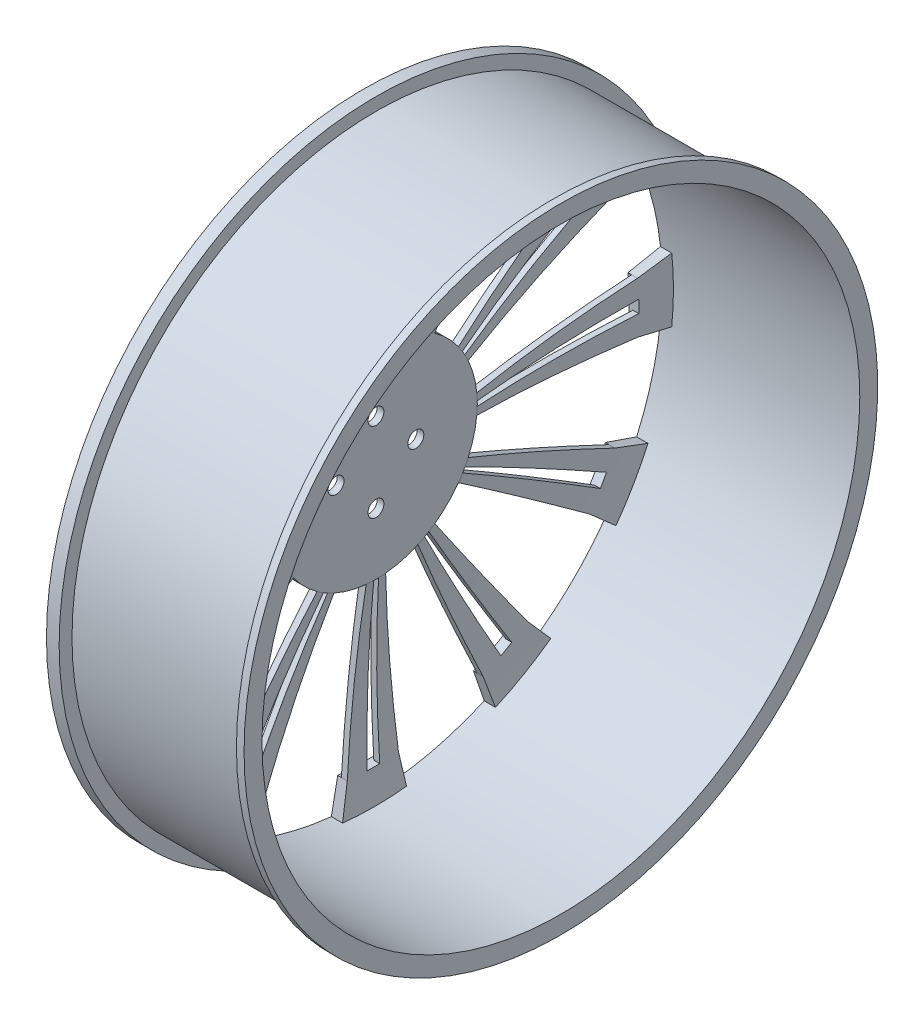
SolidWorks part; units mm, degrees
material "Stainless Steel (ferritic)"
ref_plane "Front Plane" through (0, 0, 0) normal (0, 0, 1) x (1, 0, 0)
ref_plane "Top Plane" through (0, 0, 0) normal (0, 1, 0) x (1, 0, 0)
ref_plane "Right Plane" through (0, 0, 0) normal (1, 0, 0) x (0, 0, -1)
sketch "Sketch1" plane through (0, 0, 0) normal (0, 1, 0) x (1, 0, 0)
  line L0 (0, 0) -> (0, 152.4) construction
  line L1 (-44.45, 152.4) -> (44.45, 152.4)
  line L2 (44.45, 152.4) -> (44.45, 158.8516)
  line L3 (44.45, 158.8516) -> (48.26, 158.8516)
  line L4 (48.26, 158.8516) -> (48.26, 149.86)
  line L6 (-48.26, 158.8516) -> (-48.26, 149.86)
  line L7 (-44.45, 158.8516) -> (-48.26, 158.8516)
  line L8 (-44.45, 152.4) -> (-44.45, 158.8516)
  line L11 (-115.1983, 0) -> (-44.4652, 0) construction
  line L12 (-44.4652, 50.8) -> (-44.4652, 0)
  line L13 (-47.8645, 50.8) -> (-47.8645, 0)
  line L14 (-47.8645, 0) -> (-44.4652, 0)
  line L15 (-45.1655, 149.86) -> (48.26, 149.86)
  line L16 (-44.45, 0) -> (115.1983, 0) construction
  arc A0 (-48.26, 149.86) -> (-47.8645, 50.8) centre (824.7529, 103.8144) ccw
  arc A1 (-45.1655, 149.86) -> (-44.4652, 50.8) centre (663.4897, 105.3377) ccw
  point P6 (0, 152.4)
  point P11 (0, 149.86)
  point P13 (44.45, 155.6258)
  point P26 (0, 0)
  dimension "D5" = 3.4145
  dimension "D7" = 874.2264
  dimension "D8" = 710.0525
  dimension "D1" = 3.81
  dimension "D2" = 88.9
  dimension "D3" = 152.4
  dimension "D4" = 6.4516
  dimension "D6" = 93.4255
  dimension "D9" = 50.8
  dimension "D10" = 50.8
revolve "Revolve2" add sketch "Sketch1" angle 360 about L16
sketch "Sketch2" plane through (-48.26, 0, 0) normal (-1, 0, 0) x (0, 0, 1)
  line L0 (-137.0496, 60.6253) -> (-121.3619, 55.2587)
  line L1 (-149.0011, 16.0218) -> (-132.7318, 12.8255)
  line L2 (-149.0011, -16.0218) -> (-132.7318, -12.8255)
  line L3 (-121.0278, 88.3758) -> (-108.5364, 77.4731)
  line L4 (-88.3758, 121.0278) -> (-77.4731, 108.5364)
  line L5 (-60.6253, 137.0496) -> (-55.2587, 121.3619)
  line L6 (-16.0218, 149.0011) -> (-12.8255, 132.7318)
  line L7 (16.0218, 149.0011) -> (12.8255, 132.7318)
  line L8 (60.6253, 137.0496) -> (55.2587, 121.3619)
  line L9 (88.3758, 121.0278) -> (77.4731, 108.5364)
  line L10 (121.0278, 88.3758) -> (108.5364, 77.4731)
  line L11 (137.0496, 60.6253) -> (121.3619, 55.2587)
  line L12 (149.0011, 16.0218) -> (132.7318, 12.8255)
  line L13 (149.0011, -16.0218) -> (132.7318, -12.8255)
  line L14 (137.0496, -60.6253) -> (121.3619, -55.2587)
  line L15 (121.0278, -88.3758) -> (108.5364, -77.4731)
  line L16 (88.3758, -121.0278) -> (77.4731, -108.5364)
  line L17 (60.6253, -137.0496) -> (55.2587, -121.3619)
  line L18 (16.0218, -149.0011) -> (12.8255, -132.7318)
  line L19 (-16.0218, -149.0011) -> (-12.8255, -132.7318)
  line L20 (-60.6253, -137.0496) -> (-55.2587, -121.3619)
  line L21 (-88.3758, -121.0278) -> (-77.4731, -108.5364)
  line L22 (-121.0278, -88.3758) -> (-108.5364, -77.4731)
  line L23 (-137.0496, -60.6253) -> (-121.3619, -55.2587)
  arc A1 (-132.7318, 12.8255) -> (-132.7318, -12.8255) centre (0, 0) ccw
  arc A3 (-108.5364, 77.4731) -> (-121.3619, 55.2587) centre (0, 0) ccw
  arc A5 (-55.2587, 121.3619) -> (-77.4731, 108.5364) centre (0, 0) ccw
  arc A7 (12.8255, 132.7318) -> (-12.8255, 132.7318) centre (0, 0) ccw
  arc A9 (77.4731, 108.5364) -> (55.2587, 121.3619) centre (0, 0) ccw
  arc A11 (121.3619, 55.2587) -> (108.5364, 77.4731) centre (0, 0) ccw
  arc A13 (132.7318, -12.8255) -> (132.7318, 12.8255) centre (0, 0) ccw
  arc A15 (108.5364, -77.4731) -> (121.3619, -55.2587) centre (0, 0) ccw
  arc A17 (55.2587, -121.3619) -> (77.4731, -108.5364) centre (0, 0) ccw
  arc A19 (-12.8255, -132.7318) -> (12.8255, -132.7318) centre (0, 0) ccw
  arc A21 (-77.4731, -108.5364) -> (-55.2587, -121.3619) centre (0, 0) ccw
  arc A23 (-121.3619, -55.2587) -> (-108.5364, -77.4731) centre (0, 0) ccw
  circle A24 centre (0, 0) radius 158.8516
  arc A25 (-149.0011, -16.0218) -> (-137.0496, -60.6253) centre (0, 0) ccw
  arc A26 (-137.0496, 60.6253) -> (-149.0011, 16.0218) centre (0, 0) ccw
  arc A27 (-88.3758, 121.0278) -> (-121.0278, 88.3758) centre (0, 0) ccw
  arc A28 (-16.0218, 149.0011) -> (-60.6253, 137.0496) centre (0, 0) ccw
  arc A29 (60.6253, 137.0496) -> (16.0218, 149.0011) centre (0, 0) ccw
  arc A30 (121.0278, 88.3758) -> (88.3758, 121.0278) centre (0, 0) ccw
  arc A31 (149.0011, 16.0218) -> (137.0496, 60.6253) centre (0, 0) ccw
  arc A32 (137.0496, -60.6253) -> (149.0011, -16.0218) centre (0, 0) ccw
  arc A33 (88.3758, -121.0278) -> (121.0278, -88.3758) centre (0, 0) ccw
  arc A34 (16.0218, -149.0011) -> (60.6253, -137.0496) centre (0, 0) ccw
  arc A35 (-60.6253, -137.0496) -> (-16.0218, -149.0011) centre (0, 0) ccw
  arc A36 (-121.0278, -88.3758) -> (-88.3758, -121.0278) centre (0, 0) ccw
  point P52 (0, 0)
  dimension "D1" = 12
extrude "Boss-Extrude1" add sketch "Sketch2" along normal blind 2.54
sketch "Sketch3" plane through (-50.8, 0, 0) normal (-1, 0, 0) x (0, 0, 1)
  line L0 (-46.2331, -21.0509) -> (-121.3619, -55.2587)
  line L1 (-44.6337, -24.2584) -> (-117.1635, -63.6784)
  line L2 (-41.3472, -29.5136) -> (-108.5364, -77.4731)
  line L3 (-43.4395, -26.3372) -> (-114.0287, -69.1352)
  line L4 (-50.5645, 4.8859) -> (-132.7318, 12.8255)
  line L5 (-50.7831, 1.3084) -> (-133.3058, 3.4347)
  line L6 (-50.5645, -4.8859) -> (-132.7318, -12.8255)
  line L7 (-50.7883, -1.089) -> (-133.3194, -2.8585)
  line L8 (-41.3472, 29.5136) -> (-108.5364, 77.4731)
  line L9 (-43.3253, 26.5247) -> (-113.7288, 69.6274)
  line L10 (-46.2331, 21.0509) -> (-121.3619, 55.2587)
  line L11 (-44.5285, 24.4511) -> (-116.8872, 64.1841)
  line L12 (-21.0509, 46.2331) -> (-55.2587, 121.3619)
  line L13 (-24.2584, 44.6337) -> (-63.6784, 117.1635)
  line L14 (-29.5136, 41.3472) -> (-77.4731, 108.5364)
  line L15 (-26.3372, 43.4395) -> (-69.1352, 114.0287)
  line L16 (4.8859, 50.5645) -> (12.8255, 132.7318)
  line L17 (1.3084, 50.7831) -> (3.4347, 133.3058)
  line L18 (-4.8859, 50.5645) -> (-12.8255, 132.7318)
  line L19 (-1.089, 50.7883) -> (-2.8585, 133.3194)
  line L20 (29.5136, 41.3472) -> (77.4731, 108.5364)
  line L21 (26.5247, 43.3253) -> (69.6274, 113.7288)
  line L22 (21.0509, 46.2331) -> (55.2587, 121.3619)
  line L23 (24.4511, 44.5285) -> (64.1841, 116.8872)
  line L24 (46.2331, 21.0509) -> (121.3619, 55.2587)
  line L25 (44.6337, 24.2584) -> (117.1635, 63.6784)
  line L26 (41.3472, 29.5136) -> (108.5364, 77.4731)
  line L27 (43.4395, 26.3372) -> (114.0287, 69.1352)
  line L28 (50.5645, -4.8859) -> (132.7318, -12.8255)
  line L29 (50.7831, -1.3084) -> (133.3058, -3.4347)
  line L30 (50.5645, 4.8859) -> (132.7318, 12.8255)
  line L31 (50.7883, 1.089) -> (133.3194, 2.8585)
  line L32 (41.3472, -29.5136) -> (108.5364, -77.4731)
  line L33 (43.3253, -26.5247) -> (113.7288, -69.6274)
  line L34 (46.2331, -21.0509) -> (121.3619, -55.2587)
  line L35 (44.5285, -24.4511) -> (116.8872, -64.1841)
  line L36 (21.0509, -46.2331) -> (55.2587, -121.3619)
  line L37 (24.2584, -44.6337) -> (63.6784, -117.1635)
  line L38 (29.5136, -41.3472) -> (77.4731, -108.5364)
  line L39 (26.3372, -43.4395) -> (69.1352, -114.0287)
  line L40 (-4.8859, -50.5645) -> (-12.8255, -132.7318)
  line L41 (-1.3084, -50.7831) -> (-3.4347, -133.3058)
  line L42 (4.8859, -50.5645) -> (12.8255, -132.7318)
  line L43 (1.089, -50.7883) -> (2.8585, -133.3194)
  line L44 (-29.5136, -41.3472) -> (-77.4731, -108.5364)
  line L45 (-26.5247, -43.3253) -> (-69.6274, -113.7288)
  line L46 (-21.0509, -46.2331) -> (-55.2587, -121.3619)
  line L47 (-24.4511, -44.5285) -> (-64.1841, -116.8872)
  line L48 (-132.7318, -12.8255) -> (-149.0011, -16.0218)
  line L49 (-137.0496, -60.6253) -> (-121.3619, -55.2587)
  line L50 (-121.3619, 55.2587) -> (-137.0496, 60.6253)
  line L51 (-149.0011, 16.0218) -> (-132.7318, 12.8255)
  line L52 (-77.4731, 108.5364) -> (-88.3758, 121.0278)
  line L53 (-121.0278, 88.3758) -> (-108.5364, 77.4731)
  line L54 (-12.8255, 132.7318) -> (-16.0218, 149.0011)
  line L55 (-60.6253, 137.0496) -> (-55.2587, 121.3619)
  line L56 (55.2587, 121.3619) -> (60.6253, 137.0496)
  line L57 (16.0218, 149.0011) -> (12.8255, 132.7318)
  line L58 (108.5364, 77.4731) -> (121.0278, 88.3758)
  line L59 (88.3758, 121.0278) -> (77.4731, 108.5364)
  line L60 (132.7318, 12.8255) -> (149.0011, 16.0218)
  line L61 (137.0496, 60.6253) -> (121.3619, 55.2587)
  line L62 (121.3619, -55.2587) -> (137.0496, -60.6253)
  line L63 (149.0011, -16.0218) -> (132.7318, -12.8255)
  line L64 (77.4731, -108.5364) -> (88.3758, -121.0278)
  line L65 (121.0278, -88.3758) -> (108.5364, -77.4731)
  line L66 (12.8255, -132.7318) -> (16.0218, -149.0011)
  line L67 (60.6253, -137.0496) -> (55.2587, -121.3619)
  line L68 (-55.2587, -121.3619) -> (-60.6253, -137.0496)
  line L69 (-16.0218, -149.0011) -> (-12.8255, -132.7318)
  line L70 (-108.5364, -77.4731) -> (-121.0278, -88.3758)
  line L71 (-88.3758, -121.0278) -> (-77.4731, -108.5364)
  arc A0 (-121.3619, -55.2587) -> (-108.5364, -77.4731) centre (0, 0) ccw construction
  arc A1 (-121.3619, -55.2587) -> (-108.5364, -77.4731) centre (0, 0) ccw construction
  circle A5 centre (0, 0) radius 50.8 construction
  arc A51 (-149.0011, -16.0218) -> (-137.0496, -60.6253) centre (0, 0) ccw
  arc A52 (-133.3194, -2.8585) -> (-133.3058, 3.4347) centre (0, 0) cw
  arc A53 (-50.7883, -1.089) -> (-50.7831, 1.3084) centre (0, 0) cw
  arc A54 (-50.5645, -4.8859) -> (-46.2331, -21.0509) centre (0, 0) ccw
  arc A55 (-137.0496, 60.6253) -> (-149.0011, 16.0218) centre (0, 0) ccw
  arc A56 (-88.3758, 121.0278) -> (-121.0278, 88.3758) centre (0, 0) ccw
  arc A57 (-16.0218, 149.0011) -> (-60.6253, 137.0496) centre (0, 0) ccw
  arc A58 (60.6253, 137.0496) -> (16.0218, 149.0011) centre (0, 0) ccw
  arc A59 (121.0278, 88.3758) -> (88.3758, 121.0278) centre (0, 0) ccw
  arc A60 (149.0011, 16.0218) -> (137.0496, 60.6253) centre (0, 0) ccw
  arc A61 (137.0496, -60.6253) -> (149.0011, -16.0218) centre (0, 0) ccw
  arc A62 (88.3758, -121.0278) -> (121.0278, -88.3758) centre (0, 0) ccw
  arc A63 (16.0218, -149.0011) -> (60.6253, -137.0496) centre (0, 0) ccw
  arc A64 (-60.6253, -137.0496) -> (-16.0218, -149.0011) centre (0, 0) ccw
  arc A65 (-121.0278, -88.3758) -> (-88.3758, -121.0278) centre (0, 0) ccw
  arc A66 (-137.0496, 60.6253) -> (-149.0011, 16.0218) centre (0, 0) ccw
  arc A67 (-44.5285, 24.4511) -> (-43.3253, 26.5247) centre (0, 0) cw
  arc A68 (-46.2331, 21.0509) -> (-50.5645, 4.8859) centre (0, 0) ccw
  arc A69 (-88.3758, 121.0278) -> (-121.0278, 88.3758) centre (0, 0) ccw
  arc A70 (-26.3372, 43.4395) -> (-24.2584, 44.6337) centre (0, 0) cw
  arc A71 (-29.5136, 41.3472) -> (-41.3472, 29.5136) centre (0, 0) ccw
  arc A72 (-16.0218, 149.0011) -> (-60.6253, 137.0496) centre (0, 0) ccw
  arc A73 (-1.089, 50.7883) -> (1.3084, 50.7831) centre (0, 0) cw
  arc A74 (-4.8859, 50.5645) -> (-21.0509, 46.2331) centre (0, 0) ccw
  arc A75 (60.6253, 137.0496) -> (16.0218, 149.0011) centre (0, 0) ccw
  arc A76 (24.4511, 44.5285) -> (26.5247, 43.3253) centre (0, 0) cw
  arc A77 (21.0509, 46.2331) -> (4.8859, 50.5645) centre (0, 0) ccw
  arc A78 (121.0278, 88.3758) -> (88.3758, 121.0278) centre (0, 0) ccw
  arc A79 (43.4395, 26.3372) -> (44.6337, 24.2584) centre (0, 0) cw
  arc A80 (41.3472, 29.5136) -> (29.5136, 41.3472) centre (0, 0) ccw
  arc A81 (149.0011, 16.0218) -> (137.0496, 60.6253) centre (0, 0) ccw
  arc A82 (50.7883, 1.089) -> (50.7831, -1.3084) centre (0, 0) cw
  arc A83 (50.5645, 4.8859) -> (46.2331, 21.0509) centre (0, 0) ccw
  arc A84 (137.0496, -60.6253) -> (149.0011, -16.0218) centre (0, 0) ccw
  arc A85 (44.5285, -24.4511) -> (43.3253, -26.5247) centre (0, 0) cw
  arc A86 (46.2331, -21.0509) -> (50.5645, -4.8859) centre (0, 0) ccw
  arc A87 (88.3758, -121.0278) -> (121.0278, -88.3758) centre (0, 0) ccw
  arc A88 (26.3372, -43.4395) -> (24.2584, -44.6337) centre (0, 0) cw
  arc A89 (29.5136, -41.3472) -> (41.3472, -29.5136) centre (0, 0) ccw
  arc A90 (16.0218, -149.0011) -> (60.6253, -137.0496) centre (0, 0) ccw
  arc A91 (1.089, -50.7883) -> (-1.3084, -50.7831) centre (0, 0) cw
  arc A92 (4.8859, -50.5645) -> (21.0509, -46.2331) centre (0, 0) ccw
  arc A93 (-60.6253, -137.0496) -> (-16.0218, -149.0011) centre (0, 0) ccw
  arc A94 (-24.4511, -44.5285) -> (-26.5247, -43.3253) centre (0, 0) cw
  arc A95 (-21.0509, -46.2331) -> (-4.8859, -50.5645) centre (0, 0) ccw
  arc A96 (-121.0278, -88.3758) -> (-88.3758, -121.0278) centre (0, 0) ccw
  arc A97 (-43.4395, -26.3372) -> (-44.6337, -24.2584) centre (0, 0) cw
  arc A98 (-41.3472, -29.5136) -> (-29.5136, -41.3472) centre (0, 0) ccw
  arc A103 (-117.1635, -63.6784) -> (-114.0287, -69.1352) centre (0, 0) ccw
  arc A104 (-2.8585, 133.3194) -> (3.4347, 133.3058) centre (0, 0) cw
  arc A105 (133.3194, 2.8585) -> (133.3058, -3.4347) centre (0, 0) cw
  arc A106 (2.8585, -133.3194) -> (-3.4347, -133.3058) centre (0, 0) cw
  arc A107 (-116.8872, 64.1841) -> (-113.7288, 69.6274) centre (0, 0) cw
  arc A108 (-69.1352, 114.0287) -> (-63.6784, 117.1635) centre (0, 0) cw
  arc A109 (-2.8585, 133.3194) -> (3.4347, 133.3058) centre (0, 0) cw
  arc A110 (64.1841, 116.8872) -> (69.6274, 113.7288) centre (0, 0) cw
  arc A111 (114.0287, 69.1352) -> (117.1635, 63.6784) centre (0, 0) cw
  arc A112 (133.3194, 2.8585) -> (133.3058, -3.4347) centre (0, 0) cw
  arc A113 (116.8872, -64.1841) -> (113.7288, -69.6274) centre (0, 0) cw
  arc A114 (69.1352, -114.0287) -> (63.6784, -117.1635) centre (0, 0) cw
  arc A115 (2.8585, -133.3194) -> (-3.4347, -133.3058) centre (0, 0) cw
  arc A116 (-64.1841, -116.8872) -> (-69.6274, -113.7288) centre (0, 0) cw
  arc A117 (-114.0287, -69.1352) -> (-117.1635, -63.6784) centre (0, 0) cw
  point P114 (0, 0)
  point P144 (0, 0)
  point P156 (0, 0)
  point P177 (0, 0)
  point P232 (0, 0)
  line M57 (-108.5364, 77.4731) -> (-121.0278, 88.3758)
  arc M58 (-121.0278, 88.3758) -> (-88.3758, 121.0278) centre (0, 0) cw
  line M59 (-88.3758, 121.0278) -> (-77.4731, 108.5364)
  line M61 (-55.2587, 121.3619) -> (-60.6253, 137.0496)
  arc M62 (-60.6253, 137.0496) -> (-16.0218, 149.0011) centre (0, 0) cw
  line M63 (-16.0218, 149.0011) -> (-12.8255, 132.7318)
  line M65 (12.8255, 132.7318) -> (16.0218, 149.0011)
  arc M66 (16.0218, 149.0011) -> (60.6253, 137.0496) centre (0, 0) cw
  line M67 (60.6253, 137.0496) -> (55.2587, 121.3619)
  line M69 (77.4731, 108.5364) -> (88.3758, 121.0278)
  arc M70 (88.3758, 121.0278) -> (121.0278, 88.3758) centre (0, 0) cw
  line M71 (121.0278, 88.3758) -> (108.5364, 77.4731)
  line M73 (121.3619, 55.2587) -> (137.0496, 60.6253)
  arc M74 (137.0496, 60.6253) -> (149.0011, 16.0218) centre (0, 0) cw
  line M75 (149.0011, 16.0218) -> (132.7318, 12.8255)
  line M77 (132.7318, -12.8255) -> (149.0011, -16.0218)
  arc M78 (149.0011, -16.0218) -> (137.0496, -60.6253) centre (0, 0) cw
  line M79 (137.0496, -60.6253) -> (121.3619, -55.2587)
  arc M80 (121.3619, -55.2587) -> (108.5364, -77.4731) centre (0, 0) cw
  line M81 (108.5364, -77.4731) -> (121.0278, -88.3758)
  arc M82 (121.0278, -88.3758) -> (88.3758, -121.0278) centre (0, 0) cw
  line M83 (88.3758, -121.0278) -> (77.4731, -108.5364)
  line M85 (55.2587, -121.3619) -> (60.6253, -137.0496)
  arc M86 (60.6253, -137.0496) -> (16.0218, -149.0011) centre (0, 0) cw
  line M87 (16.0218, -149.0011) -> (12.8255, -132.7318)
  arc M88 (12.8255, -132.7318) -> (-12.8255, -132.7318) centre (0, 0) cw
  line M89 (-12.8255, -132.7318) -> (-16.0218, -149.0011)
  arc M90 (-16.0218, -149.0011) -> (-60.6253, -137.0496) centre (0, 0) cw
  line M91 (-60.6253, -137.0496) -> (-55.2587, -121.3619)
  arc M92 (-55.2587, -121.3619) -> (-77.4731, -108.5364) centre (0, 0) cw
  line M93 (-77.4731, -108.5364) -> (-88.3758, -121.0278)
  arc M94 (-88.3758, -121.0278) -> (-121.0278, -88.3758) centre (0, 0) cw
  line M95 (-121.0278, -88.3758) -> (-108.5364, -77.4731)
  arc M96 (-108.5364, -77.4731) -> (-121.3619, -55.2587) centre (0, 0) cw
  line M97 (-121.3619, -55.2587) -> (-137.0496, -60.6253)
  arc M98 (-137.0496, -60.6253) -> (-149.0011, -16.0218) centre (0, 0) cw
  line M99 (-149.0011, -16.0218) -> (-132.7318, -12.8255)
  line M101 (-132.7318, 12.8255) -> (-149.0011, 16.0218)
  arc M102 (-149.0011, 16.0218) -> (-137.0496, 60.6253) centre (0, 0) cw
  line M103 (-137.0496, 60.6253) -> (-121.3619, 55.2587)
  arc M104 (-121.3619, 55.2587) -> (-108.5364, 77.4731) centre (0, 0) cw
  dimension "D1" = 12
  dimension "D2" = 12
  dimension "D4" = 4
  dimension "D3" = 12
  dimension "D5" = 12
extrude "Cut-Extrude1" cut sketch "Sketch3" against normal through all contours A54 L6 L0 M99 M98 M97 | A68 L10 L4 M103 M102 M101 | A71 L14 L8 M59 M58 M57 | L11 A67 L9 M104 | A74 L18 L12 M63 M62 M61 | A77 L22 L16 M67 M66 M65 | A80 L26 L20 M71 M70 M69 | A83 L30 L24 M75 M74 M73 | A86 L34 L28 M79 M78 M77 | A89 L38 L32 M83 M82 M81 | L35 A85 L33 M80 | A92 L42 L36 M87 M86 M85 | L43 A91 L41 M88 | A95 L46 L40 M91 M90 M89 | L47 A94 L45 M92 | A98 L2 L44 M95 M94 M93 | L3 A97 L1 M96 | L5 A52 L7 A53 | L13 A108 L15 A70 | L17 A104 L19 A73 | L21 A110 L23 A76 | L27 A111 L25 A79 | L29 A105 L31 A82 | L37 A114 L39 A88
sketch "Sketch4" plane through (-44.4652, 0, 0) normal (1, 0, 0) x (0, 0, -1)
  circle A1 centre (0, 0) radius 20 construction
  circle A2 centre (0, -20) radius 4
  circle A3 centre (20, 0) radius 4
  circle A4 centre (0, 20) radius 4
  circle A5 centre (-20, 0) radius 4
extrude "Cut-Extrude2" cut sketch "Sketch4" against normal through all
